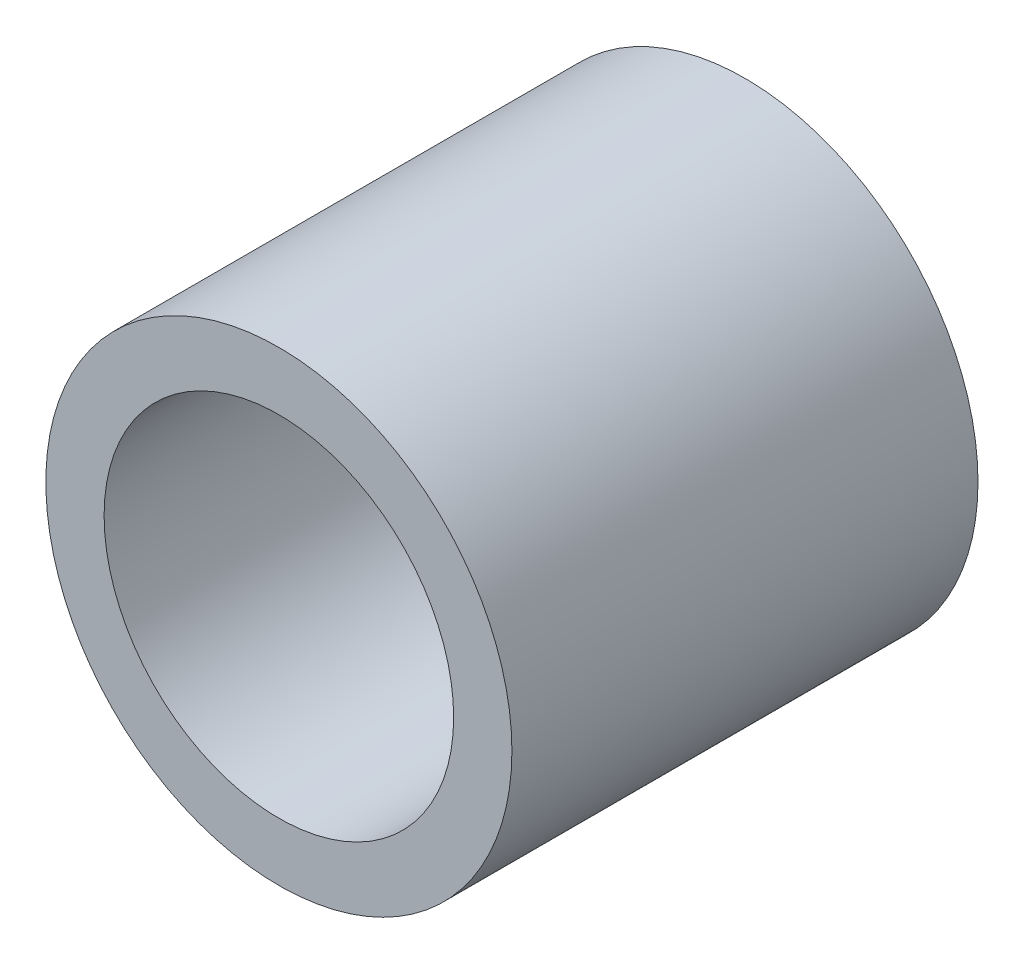
SolidWorks part; units mm, degrees
ref_plane "Front Plane" through (0, 0, 0) normal (0, 0, 1) x (1, 0, 0)
ref_plane "Top Plane" through (0, 0, 0) normal (0, 1, 0) x (1, 0, 0)
ref_plane "Right Plane" through (0, 0, 0) normal (1, 0, 0) x (0, 0, -1)
sketch "Sketch1" plane through (0, 0, 0) normal (0, 0, 1) x (1, 0, 0)
  circle A0 centre (0, 0) radius 12.7
  circle A1 centre (0, 0) radius 9.525
  dimension "D1" = 19.05
  dimension "D2" = 25.4
extrude "Boss-Extrude1" add sketch "Sketch1" along normal mid plane 25.4
